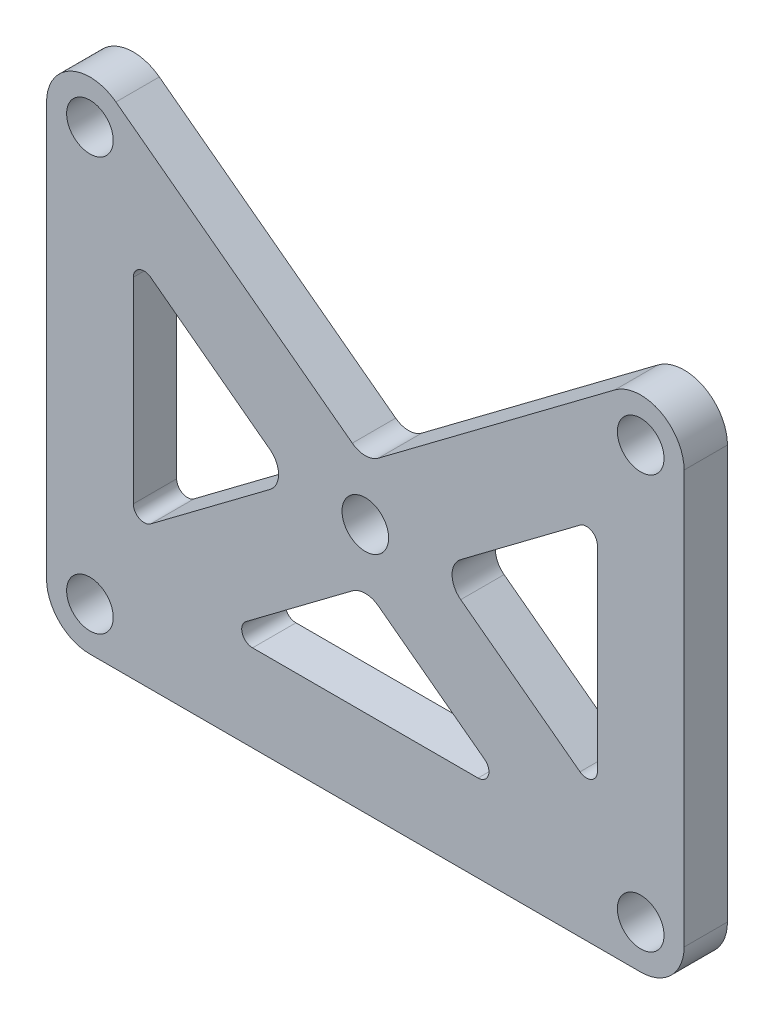
SolidWorks part; units mm, degrees
ref_plane "Front Plane" through (0, 0, 0) normal (0, 0, 1) x (1, 0, 0)
ref_plane "Top Plane" through (0, 0, 0) normal (0, 1, 0) x (1, 0, 0)
ref_plane "Right Plane" through (0, 0, 0) normal (1, 0, 0) x (0, 0, -1)
sketch "Sketch1" plane through (0, 0, 0) normal (0, 0, 1) x (1, 0, 0)
  line L0 (0, 0) -> (50.8, 38.1) construction
  line L1 (0, 38.1) -> (50.8, 0) construction
  line L2 (2.4, -3.2) -> (53.2, 34.9)
  line L3 (-2.4, 34.9) -> (48.4, -3.2)
  line L4 (-2.4, 3.2) -> (48.4, 41.3)
  line L5 (2.4, 41.3) -> (53.2, 3.2)
  line L6 (0, 0) -> (50.8, 0) construction
  line L7 (0, 38.1) -> (0, 0) construction
  line L8 (50.8, 38.1) -> (50.8, 0) construction
  line L9 (46.8, 38.1) -> (46.8, 4)
  line L10 (4, 4) -> (46.8, 4)
  line L11 (4, 38.1) -> (4, 4)
  line L12 (54.8, 38.1) -> (54.8, -4)
  line L13 (-4, -4) -> (54.8, -4)
  line L14 (-4, 38.1) -> (-4, -4)
  arc A0 (2.4, -3.2) -> (-2.4, 3.2) centre (0, 0) cw
  arc A1 (53.2, 34.9) -> (48.4, 41.3) centre (50.8, 38.1) ccw
  arc A2 (-2.4, 34.9) -> (2.4, 41.3) centre (0, 38.1) cw
  arc A3 (48.4, -3.2) -> (53.2, 3.2) centre (50.8, 0) ccw
  circle A4 centre (0, 0) radius 2.15
  circle A8 centre (25.4, 19.05) radius 2.15
  circle A9 centre (0, 38.1) radius 2.15
  circle A10 centre (50.8, 38.1) radius 2.15
  circle A11 centre (50.8, 0) radius 2.15
  point P5 (25.4, 19.05)
  dimension "D5" = 4.3
  dimension "D1" = 38.1
  dimension "D2" = 50.8
  dimension "D3" = 4
  dimension "D4" = 4
  dimension "D6" = 4
  dimension "D7" = 4
extrude "Boss-Extrude1" add sketch "Sketch1" along normal blind 4
fillet "Fillet1" radius 2 4 edges at (25.4, 14.05, 2) (32.0667, 19.05, 2) (18.7333, 19.05, 2) (25.4, 24.05, 2)
fillet "Fillet3" radius 1 6 edges at (46.8, 8, 2) (46.8, 30.1, 2) (38.8, 4, 2) (12, 4, 2) (4, 8, 2) (4, 30.1, 2)
